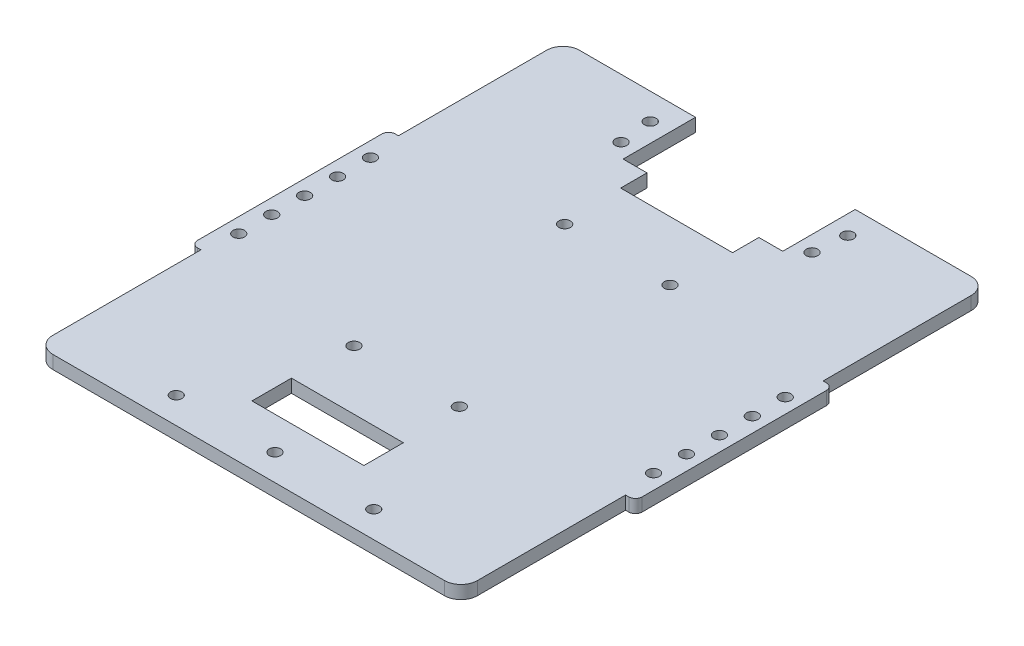
SolidWorks part; units mm, degrees
ref_plane "前视基准面" through (0, 0, 0) normal (0, 0, 1) x (1, 0, 0)
ref_plane "上视基准面" through (0, 0, 0) normal (0, 1, 0) x (1, 0, 0)
ref_plane "右视基准面" through (0, 0, 0) normal (1, 0, 0) x (0, 0, -1)
sketch "草图1" plane through (0, 0, 0) normal (0, 1, 0) x (1, 0, 0)
  line L1 (-67.5, 50) -> (67.5, 50)
  line L2 (-67.5, 50) -> (-67.5, -50)
  line L3 (-67.5, -50) -> (67.5, -50)
  line L4 (67.5, 50) -> (67.5, -50)
  line L5 (-67.5, 50) -> (67.5, -50) construction
  line L6 (-67.5, -50) -> (67.5, 50) construction
  point P0 (0, 0)
  dimension "D1" = 100
  dimension "D2" = 135
extrude "凸台-拉伸1" add sketch "草图1" along normal blind 4
sketch "草图2" plane through (0, 0, 50) normal (0, 0, 1) x (1, 0, 0)
  line L4 (-67.5, 0) -> (67.5, 0)
  line L5 (67.5, 0) -> (67.5, 4)
  line L6 (67.5, 4) -> (-67.5, 4)
  line L7 (-67.5, 4) -> (-67.5, 0)
  line L8 (-67.5, 0) -> (67.5, 0)
  line L9 (67.5, 0) -> (67.5, 4)
  line L10 (67.5, 4) -> (-67.5, 4)
  line L11 (-67.5, 4) -> (-67.5, 0)
  dimension "D1" = 0
extrude "凸台-拉伸2" add sketch "草图2" along normal blind 60
sketch "草图3" plane through (0, 4, 0) normal (0, 1, 0) x (1, 0, 0)
  line L1 (-67.5, 50) -> (-64.5, 50)
  line L2 (-67.5, 50) -> (-67.5, 0)
  line L3 (-67.5, 0) -> (-64.5, 0)
  line L4 (-64.5, 50) -> (-64.5, 0)
  line L5 (67.5, 50) -> (64.5, 50)
  line L6 (67.5, 50) -> (67.5, 0)
  line L7 (67.5, 0) -> (64.5, 0)
  line L8 (64.5, 50) -> (64.5, 0)
  line L9 (-67.5, -110) -> (-64.5, -110)
  line L10 (-67.5, -110) -> (-67.5, -60)
  line L11 (-67.5, -60) -> (-64.5, -60)
  line L12 (-64.5, -110) -> (-64.5, -60)
  line L13 (67.5, -110) -> (64.5, -110)
  line L14 (67.5, -110) -> (67.5, -60)
  line L15 (67.5, -60) -> (64.5, -60)
  line L16 (64.5, -110) -> (64.5, -60)
  dimension "D1" = 50
  dimension "D2" = 3
  dimension "D3" = 3
  dimension "D4" = 50
  dimension "D5" = 3
  dimension "D6" = 3
  dimension "D7" = 50
extrude "切除-拉伸1" cut sketch "草图3" against normal through all both and the other way through all
fillet "圆角1" radius 5 4 edges at (-64.5, 2, 110) (64.5, 2, 110) (64.5, 2, -50) (-64.5, 2, -50)
fillet "圆角2" radius 2 4 edges at (67.5, 2, 60) (67.5, 2, 0) (-67.5, 2, 60) (-67.5, 2, 0)
sketch "草图4" plane through (0, 4, 0) normal (0, 1, 0) x (1, 0, 0)
  circle A0 centre (-30, -102) radius 1.75
  circle A1 centre (0, -102) radius 1.75
  circle A2 centre (30, -102) radius 1.75
  circle A3 centre (-30, 42) radius 1.75
  circle A4 centre (0, 42) radius 1.75
  circle A5 centre (30, 42) radius 1.75
extrude "切除-拉伸2" cut sketch "草图4" against normal through all both and the other way through all
sketch "草图5" plane through (0, 4, 0) normal (0, 1, 0) x (1, 0, 0)
  line L1 (-17, -92) -> (17, -92)
  line L2 (-17, -92) -> (-17, -80)
  line L3 (-17, -80) -> (17, -80)
  line L4 (17, -92) -> (17, -80)
  line L5 (-17, 20) -> (17, 20)
  line L6 (-17, 20) -> (-17, 32)
  line L7 (-17, 32) -> (17, 32)
  line L8 (17, 20) -> (17, 32)
extrude "切除-拉伸3" cut sketch "草图5" against normal through all both and the other way through all
sketch "草图6" plane through (0, 0, 0) normal (0, -1, 0) x (1, 0, 0)
  circle A0 centre (-16, -2) radius 1.75
  circle A1 centre (16, -2) radius 1.75
  circle A2 centre (16, 62) radius 1.75
  circle A3 centre (-16, 62) radius 1.75
  dimension "D1" = 3.5
  dimension "D2" = 3.5
  dimension "D3" = 3.5
  dimension "D4" = 3.5
extrude "切除-拉伸4" cut sketch "草图6" against normal through all both and the other way through all
sketch "草图7" plane through (0, 0, -50) normal (0, 0, -1) x (-1, 0, 0)
  line L0 (59.5, 0) -> (-59.5, 4) construction
  line L1 (-59.5, 0) -> (59.5, 0) construction
  line L6 (24.25, 3.5) -> (-24.25, 0.5) construction
  line L7 (24.25, 0.5) -> (-24.25, 3.5) construction
  line L8 (-24.25, 4) -> (24.25, 4)
  line L9 (-24.25, 4) -> (-24.25, 0)
  line L10 (-24.25, 0) -> (24.25, 0)
  line L11 (24.25, 4) -> (24.25, 0)
  line L12 (-24.25, 4) -> (24.25, 0) construction
  line L13 (-24.25, 0) -> (24.25, 4) construction
  point P4 (0, 2)
  point P9 (0, 2)
  dimension "D1" = 48.5
  dimension "D2" = 3
extrude "切除-拉伸5" cut sketch "草图7" against normal blind 22
sketch "草图8" plane through (0, 0, 0) normal (0, -1, 0) x (1, 0, 0)
  circle A0 centre (-29, -32.13) radius 1.75
  circle A1 centre (29, -32.13) radius 1.75
extrude "切除-拉伸6" cut sketch "草图8" against normal through all both and the other way through all
sketch "草图9" plane through (0, 4, 0) normal (0, 1, 0) x (1, 0, 0)
  line L0 (-67.5, -30) -> (67.5, -30) construction
  line L1 (-67.5, -2) -> (-67.5, -58) construction
  line L2 (67.5, -58) -> (67.5, -2) construction
  line L3 (0, -30) -> (0, -9.8669) construction
  circle A0 centre (-63, -30) radius 1.75
  circle A1 centre (-63, -20) radius 1.75
  circle A2 centre (-63, -10) radius 1.75
  circle A3 centre (-63, -40) radius 1.75
  circle A4 centre (-63, -50) radius 1.75
  circle A5 centre (63, -50) radius 1.75
  circle A6 centre (63, -40) radius 1.75
  circle A7 centre (63, -30) radius 1.75
  circle A8 centre (63, -20) radius 1.75
  circle A9 centre (63, -10) radius 1.75
  dimension "D1" = 3.5
  dimension "D2" = 4.5
  dimension "D3" = 3
extrude "切除-拉伸7" cut sketch "草图9" against normal through all both and the other way through all
